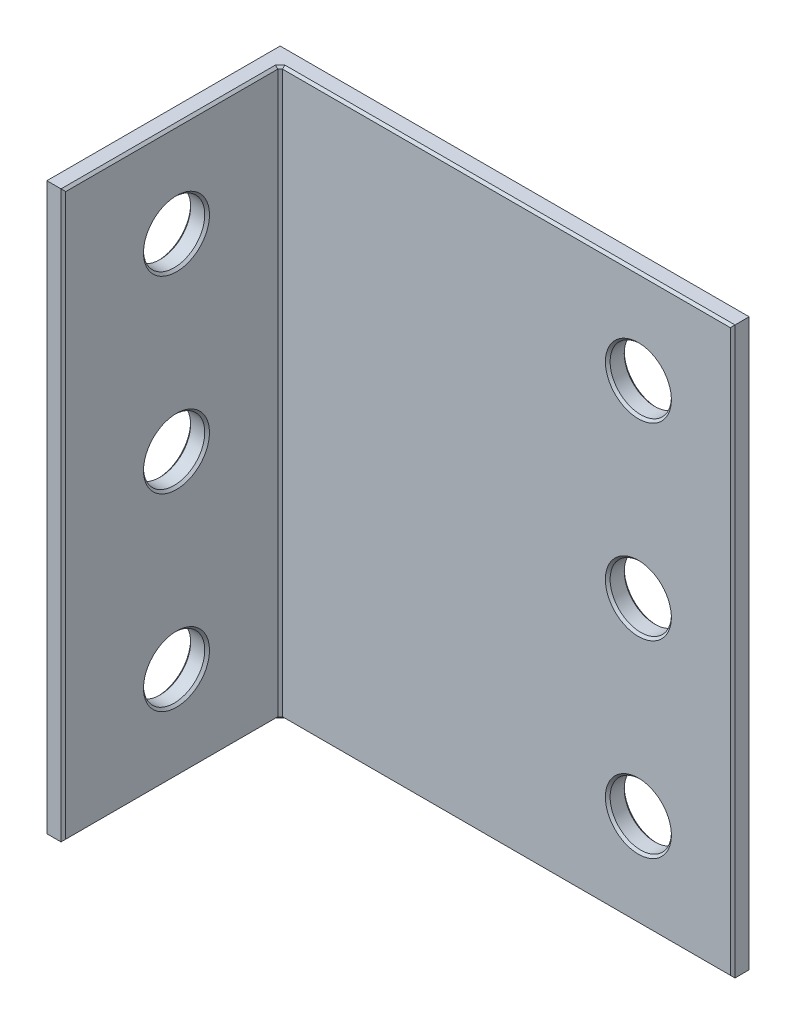
SolidWorks part; units mm, degrees
ref_plane "前视" through (0, 0, 0) normal (0, 0, 1) x (1, 0, 0)
ref_plane "上视" through (0, 0, 0) normal (0, 1, 0) x (1, 0, 0)
ref_plane "右视" through (0, 0, 0) normal (1, 0, 0) x (0, 0, -1)
sketch "草图1" plane through (0, 0, 0) normal (0, 0, 1) x (1, 0, 0)
  line L0 (160, 281.9635) -> (160, -120.4694) construction
  line L1 (0, 0) -> (200, 0)
  line L2 (0, 0) -> (0, 240)
  line L3 (0, 240) -> (200, 240)
  line L4 (200, 0) -> (200, 240)
  circle A0 centre (160, 40) radius 13
  circle A1 centre (160, 120) radius 13
  circle A2 centre (160, 200) radius 13
  dimension "D7" = 26
  dimension "D1" = 240
  dimension "D2" = 200
  dimension "D3" = 160
  dimension "D4" = 40
  dimension "D5" = 80
  dimension "D6" = 80
extrude "基体-拉伸" add sketch "草图1" along normal blind 8
sketch "草图2" plane through (0, 0, 8) normal (0, 0, 1) x (1, 0, 0)
  line L1 (0, 240) -> (8, 240)
  line L2 (0, 240) -> (0, 0)
  line L3 (0, 0) -> (8, 0)
  line L4 (8, 240) -> (8, 0)
  dimension "D1" = 8
extrude "凸台-拉伸1" add sketch "草图2" along normal blind 92
sketch "草图3" plane through (0, 0, 0) normal (-1, 0, 0) x (0, 0, 1)
  line L0 (52, 245.7913) -> (52, 32.4579) construction
  line L1 (0, 240) -> (0, 0) construction
  line L2 (100, 240) -> (0, 240) construction
  circle A0 centre (52, 200) radius 13
  circle A1 centre (52, 120) radius 13
  circle A2 centre (52, 40) radius 13
  dimension "D5" = 26
  dimension "D1" = 52
  dimension "D2" = 40
  dimension "D3" = 80
  dimension "D4" = 80
extrude "切除-拉伸1" cut sketch "草图3" against normal through all
chamfer "倒角1" distance 1 angle 45 26 edges at (173, 200, 0) (173, 40, 0) (173, 120, 0) (173, 120, 8) (173, 40, 8) (173, 200, 8) (100, 0, 0) (200, 120, 0) (100, 240, 0) (0, 240, 50) (0, 120, 100) (0, 0, 50) (0, 120, 0) (0, 200, 65) (0, 120, 65) (0, 40, 65) (200, 120, 8) (8, 120, 100) (8, 187, 52) (8, 107, 52) (8, 27, 52)
